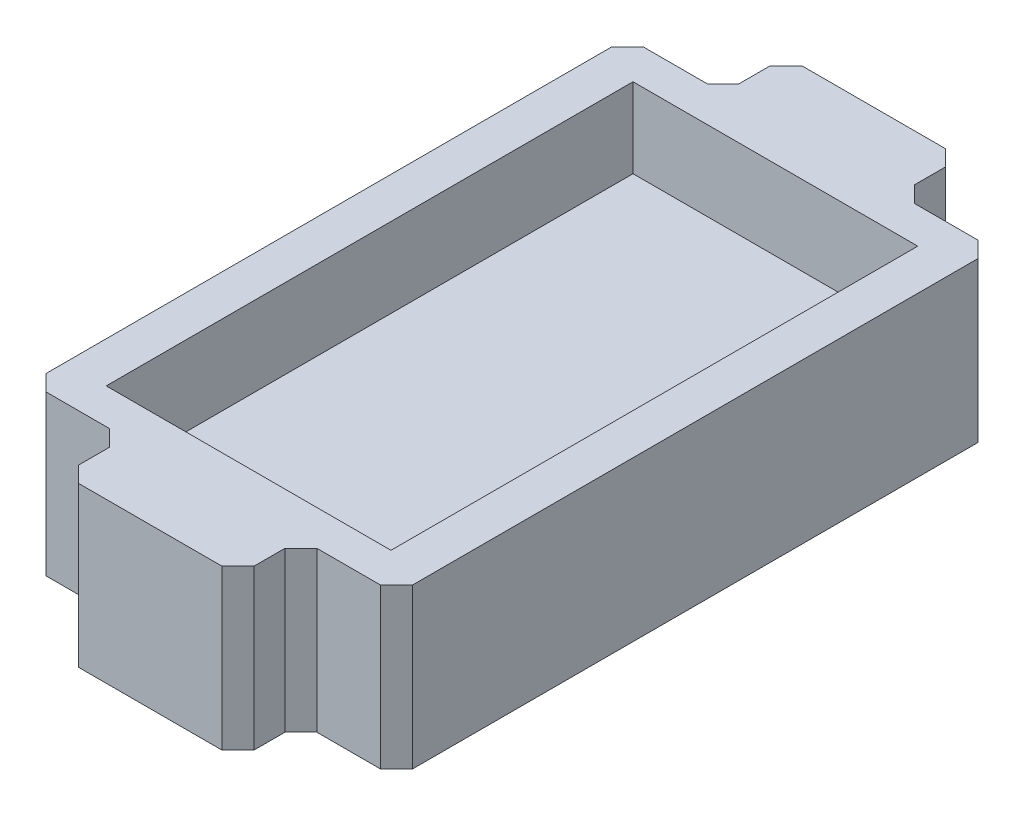
SolidWorks part; units mm, degrees
material "1.4000 (X6Cr13)"
ref_plane "正面" through (0, 0, 0) normal (0, 0, 1) x (1, 0, 0)
ref_plane "平面" through (0, 0, 0) normal (0, 1, 0) x (1, 0, 0)
ref_plane "右側面" through (0, 0, 0) normal (1, 0, 0) x (0, 0, -1)
sketch "ｽｹｯﾁ1" plane through (0, 0, 0) normal (0, 1, 0) x (1, 0, 0)
  line L0 (0, 0) -> (23, 0)
  line L1 (23, 0) -> (23, 37.5)
  line L2 (23, 37.5) -> (0, 37.5)
  line L3 (0, 37.5) -> (0, 0)
  line L4 (11.5, 37.5) -> (11.5, 41.45)
  line L5 (11.5, 41.45) -> (17, 41.45)
  line L6 (17, 41.45) -> (17, 37.5)
  line L7 (11.5, 41.45) -> (6, 41.45)
  line L8 (6, 41.45) -> (6, 37.5)
  line L9 (0, 18.75) -> (23, 18.75) construction
  line L10 (6, -3.95) -> (6, 0)
  line L11 (11.5, -3.95) -> (6, -3.95)
  line L12 (17, -3.95) -> (17, 0)
  line L13 (11.5, -3.95) -> (17, -3.95)
  line L14 (11.5, 0) -> (11.5, -3.95)
extrude "ﾎﾞｽ - 押し出し1" add sketch "ｽｹｯﾁ1" along normal blind 10 contours L3 L9 L1 L2 | L9 L3 L0 L1 | L0 L14 L13 L12 | L14 L0 L10 L11 | L6 L5 L4 L2 | L7 L8 L2 L4
chamfer "面取り1" distance 1 distance2 1 12 edges at (23, 5, 0) (17, 5, 0) (17, 5, 3.95) (6, 5, 3.95) (6, 5, 0) (0, 5, 0) (0, 5, -37.5) (6, 5, -37.5) (6, 5, -41.45) (17, 5, -41.45) (23, 5, -37.5) (17, 5, -37.5)
sketch "ｽｹｯﾁ2" plane through (0, 10, 0) normal (0, 1, 0) x (1, 0, 0)
  line L0 (23, 18.75) -> (0, 18.75)
  line L1 (23, 1) -> (23, 36.5) construction
  line L2 (0, 36.5) -> (0, 1) construction
  line L3 (11.5, 18.75) -> (11.5, 0)
  line L4 (11.5, 18.75) -> (11.5, 37.5)
  line L6 (20.4369, 2.2166) -> (2.5631, 2.2166)
  line L7 (20.4369, 2.2166) -> (20.4369, 35.2834)
  line L8 (20.4369, 35.2834) -> (2.5631, 35.2834)
  line L9 (2.5631, 2.2166) -> (2.5631, 35.2834)
  line L10 (20.4369, 2.2166) -> (2.5631, 35.2834) construction
  line L11 (20.4369, 35.2834) -> (2.5631, 2.2166) construction
extrude "ｶｯﾄ - 押し出し1" cut sketch "ｽｹｯﾁ2" against normal blind 5 contours L9 L6 L3 L0 | L6 L7 L0 L3 | L7 L8 L4 L0 | L9 L0 L4 L8
